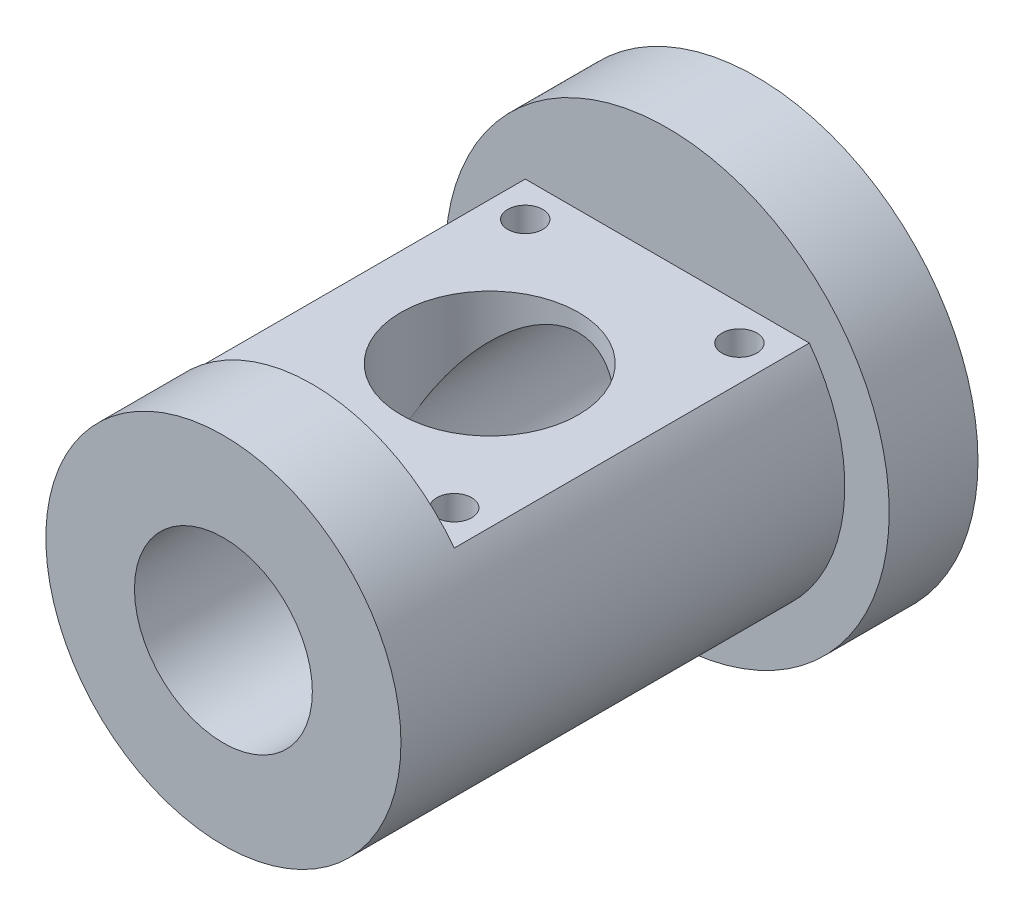
SolidWorks part; units mm, degrees
ref_plane "Front Plane" through (0, 0, 0) normal (0, 0, 1) x (1, 0, 0)
ref_plane "Top Plane" through (0, 0, 0) normal (0, 1, 0) x (1, 0, 0)
ref_plane "Right Plane" through (0, 0, 0) normal (1, 0, 0) x (0, 0, -1)
sketch "Sketch1" plane through (0, 0, 0) normal (0, 0, 1) x (1, 0, 0)
  circle A0 centre (0, 0) radius 25.4
  circle A1 centre (0, 0) radius 25.4508
  circle A2 centre (0, 0) radius 12.7254
  dimension "D1" = 50.8
  dimension "D2" = 25.4508
extrude "Boss-Extrude1" add sketch "Sketch1" along normal blind 76.2 contours A0 A2
sketch "Sketch2" plane through (0, 0, 0) normal (0, 1, 0) x (1, 0, 0)
  line L0 (0, -76.2) -> (0, 0) construction
  line L1 (-25.4, -76.2) -> (25.4, -76.2) construction
  line L3 (-12.7, -25.4) -> (12.7, -25.4) construction
  line L4 (-12.7, -25.4) -> (-12.7, -50.8) construction
  line L5 (-12.7, -50.8) -> (12.7, -50.8) construction
  line L6 (12.7, -25.4) -> (12.7, -50.8) construction
  line L7 (-12.7, -25.4) -> (12.7, -50.8) construction
  line L8 (-12.7, -50.8) -> (12.7, -25.4) construction
  circle A0 centre (0, -38.1) radius 12.7
  point P5 (0, -38.1)
  dimension "D1" = 25.4
  dimension "D2" = 25.4
  dimension "D3" = 25.4
sketch "Sketch3" plane through (0, 0, 0) normal (0, 0, -1) x (-1, 0, 0)
  circle A0 centre (0, 0) radius 31.75
  circle A1 centre (0, 0) radius 12.7254 construction
  circle A2 centre (0, 0) radius 12.7254
  dimension "D1" = 63.5
extrude "Boss-Extrude2" add sketch "Sketch3" against normal blind 12.7
ref_plane "Plane1" through (0, 25.4, 0) normal (0, 1, 0) x (1, 0, 0)
extrude "Cut-Extrude3" cut sketch "Sketch2" along normal up to next
sketch "Sketch5" plane through (0, 25.4, 0) normal (0, 1, 0) x (1, 0, 0)
  line L1 (-25.4, -63.5) -> (25.4, -63.5)
  line L2 (-25.4, -63.5) -> (-25.4, -12.7)
  line L3 (-25.4, -12.7) -> (25.4, -12.7)
  line L4 (25.4, -63.5) -> (25.4, -12.7)
  line L5 (-25.4, -63.5) -> (25.4, -12.7) construction
  line L6 (-25.4, -12.7) -> (25.4, -63.5) construction
  point P0 (0, -38.1)
extrude "Cut-Extrude4" cut sketch "Sketch5" against normal blind 10.16
sketch "Sketch7" plane through (0, 0, 0) normal (0, 0, -1) x (-1, 0, 0)
  circle A0 centre (0, 0) radius 25.4 construction
  circle A1 centre (0, 25.4) radius 2.665
  circle A2 centre (21.997, 12.7) radius 2.665
  circle A3 centre (21.997, -12.7) radius 2.665
  circle A4 centre (0, -25.4) radius 2.665
  circle A5 centre (-21.997, -12.7) radius 2.665
  circle A6 centre (-21.997, 12.7) radius 2.665
  point P18 (0, 0)
  dimension "D1" = 50.8
  dimension "D2" = 5.33
  dimension "D3" = 6
extrude "Cut-Extrude6" cut sketch "Sketch7" against normal blind 6.35
sketch "Sketch8" plane through (0, 15.24, 0) normal (0, 1, 0) x (1, 0, 0)
  line L0 (-15.32, -12.7) -> (-15.32, -17.7) construction
  line L1 (20.32, -12.7) -> (-20.32, -12.7) construction
  line L2 (-15.32, -17.7) -> (-20.32, -17.7) construction
  line L3 (-20.32, -63.5) -> (-20.32, -12.7) construction
  line L4 (20.32, -38.1) -> (-20.32, -38.1) construction
  line L5 (20.32, -12.7) -> (20.32, -63.5) construction
  line L6 (0, -63.5) -> (0, -12.7) construction
  line L7 (20.32, -63.5) -> (-20.32, -63.5) construction
  circle A0 centre (-15.32, -17.7) radius 2.5
  circle A1 centre (15.32, -17.7) radius 2.5
  circle A2 centre (-15.32, -58.5) radius 2.5
  circle A3 centre (15.32, -58.5) radius 2.5
  dimension "D2" = 5
  dimension "D1" = 5
extrude "Cut-Extrude7" cut sketch "Sketch8" against normal blind 6.35
